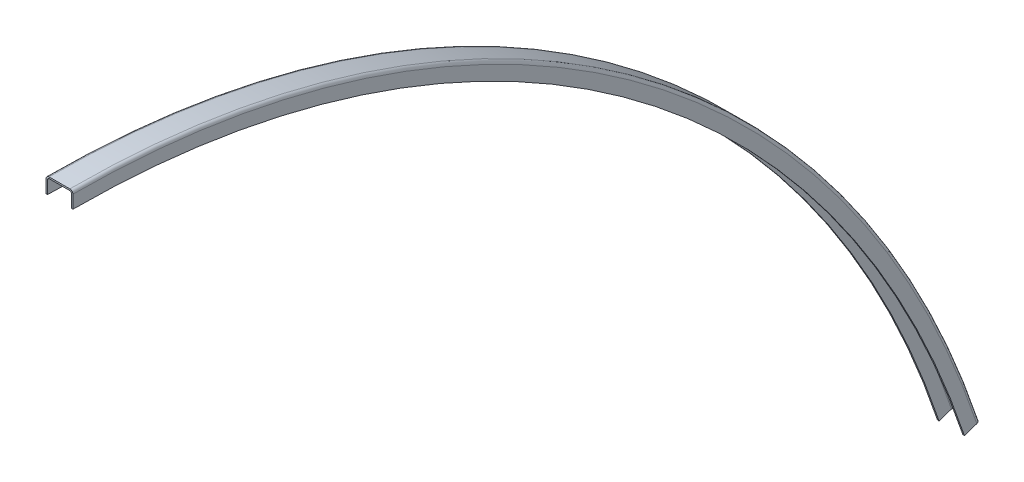
SolidWorks part; units mm, degrees
material "Galvanized Steel"
ref_plane "Front Plane" through (0, 0, 0) normal (0, 0, 1) x (1, 0, 0)
ref_plane "Top Plane" through (0, 0, 0) normal (0, 1, 0) x (1, 0, 0)
ref_plane "Right Plane" through (0, 0, 0) normal (1, 0, 0) x (0, 0, -1)
sketch "Sketch1" plane through (0, 0, 0) normal (0, 0, 1) x (1, 0, 0)
  line L0 (-23.2037, 37.9815) -> (-23.2037, 54.9815)
  line L1 (-19.2037, 58.9815) -> (7.7963, 58.9815)
  line L2 (11.7963, 54.9815) -> (11.7963, 37.9815)
  line L3 (11.7963, 37.9815) -> (9.7963, 37.9815)
  line L4 (9.7963, 37.9815) -> (9.7963, 54.9815)
  line L5 (7.7963, 56.9815) -> (-19.2037, 56.9815)
  line L6 (-21.2037, 54.9815) -> (-21.2037, 37.9815)
  line L7 (-21.2037, 37.9815) -> (-23.2037, 37.9815)
  line L8 (14.4794, -1185.5185) -> (-23.2037, -1185.5185) construction
  arc A0 (9.7963, 54.9815) -> (7.7963, 56.9815) centre (7.7963, 54.9815) ccw
  arc A1 (-21.2037, 54.9815) -> (-19.2037, 56.9815) centre (-19.2037, 54.9815) cw
  arc A2 (7.7963, 58.9815) -> (11.7963, 54.9815) centre (7.7963, 54.9815) cw
  arc A3 (-23.2037, 54.9815) -> (-19.2037, 58.9815) centre (-19.2037, 54.9815) cw
  point P14 (11.7963, 58.9815)
  point P17 (-23.2037, 58.9815)
  dimension "D7" = 2
  dimension "D8" = 4
  dimension "D1" = 35
  dimension "D2" = 21
  dimension "D3" = 21
  dimension "D4" = 1244.5
  dimension "D6" = 2
revolve "Revolve1" add sketch "Sketch1" angle 71.5 about L8
